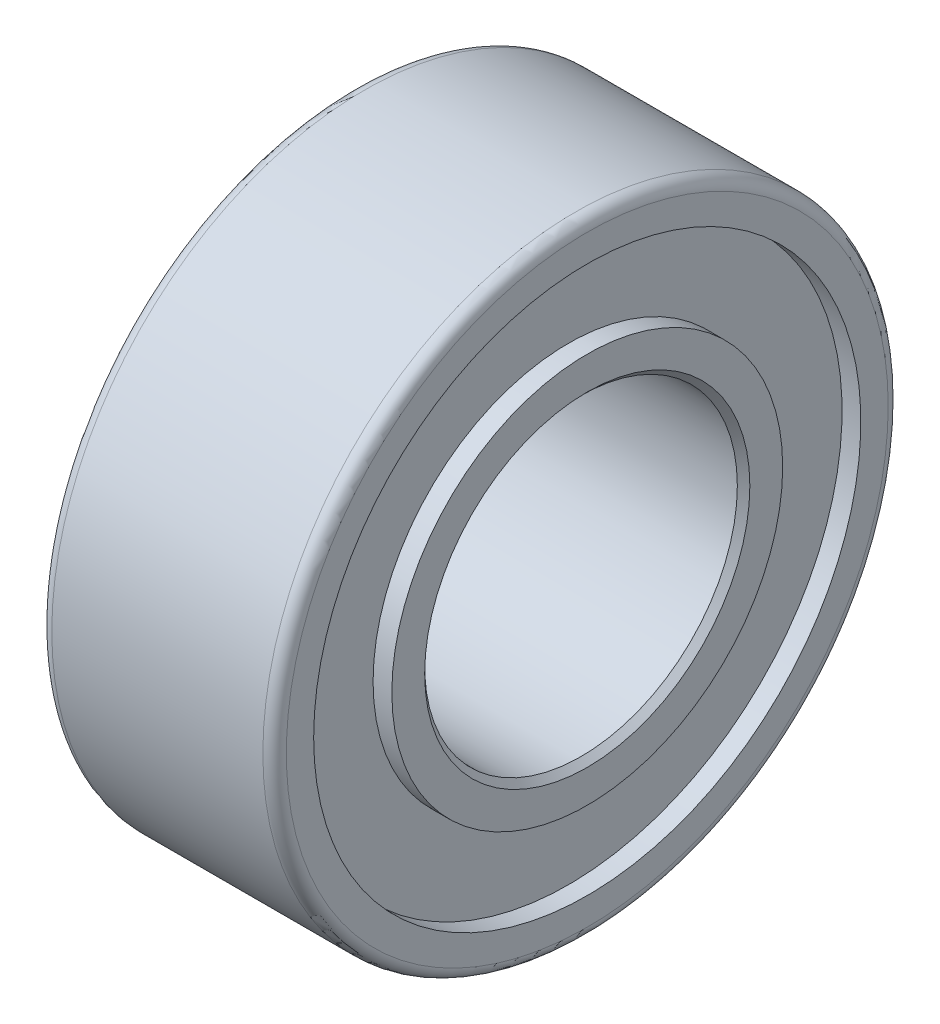
SolidWorks part; units mm, degrees
material "Plain Carbon Steel"
ref_plane "Front Plane" through (0, 0, 0) normal (0, 0, 1) x (1, 0, 0)
ref_plane "Top Plane" through (0, 0, 0) normal (0, 1, 0) x (1, 0, 0)
ref_plane "Right Plane" through (0, 0, 0) normal (1, 0, 0) x (0, 0, -1)
ref_plane "Plane1" through (-2.3812, 0, 0) normal (-1, 0, 0) x (0, -1, 0)
sketch "Sketch1" plane through (-2.3812, 0, 0) normal (-1, 0, 0) x (0, -1, 0)
  circle A0 centre (0, 0) radius 6.35
extrude "Boss-Extrude1" add sketch "Sketch1" against normal blind 4.7625
sketch "Sketch2" plane through (2.3813, 0, 0) normal (1, 0, 0) x (0, 0, -1)
  circle A0 centre (0, 0) radius 3.175
extrude "Cut-Extrude1" cut sketch "Sketch2" against normal through all
sketch "Sketch3" plane through (-2.3812, 0, 0) normal (-1, 0, 0) x (0, 0, 1)
  circle A0 centre (0, 0) radius 5.5563
  circle A1 centre (0, 0) radius 3.9688
extrude "Cut-Extrude2" cut sketch "Sketch3" against normal blind 0.381
sketch "Sketch4" plane through (2.3813, 0, 0) normal (1, 0, 0) x (0, 0, -1)
  circle A0 centre (0, 0) radius 5.5563
  circle A1 centre (0, 0) radius 3.9688
extrude "Cut-Extrude3" cut sketch "Sketch4" against normal blind 0.381
chamfer "Chamfer1" distance 0.127 angle 45 2 edges at (2.3813, 0, 3.175) (-2.3812, 0, 3.175)
fillet "Fillet1" radius 0.2381 2 edges at (-2.3812, 0, -6.35) (2.3813, 0, -6.35)
